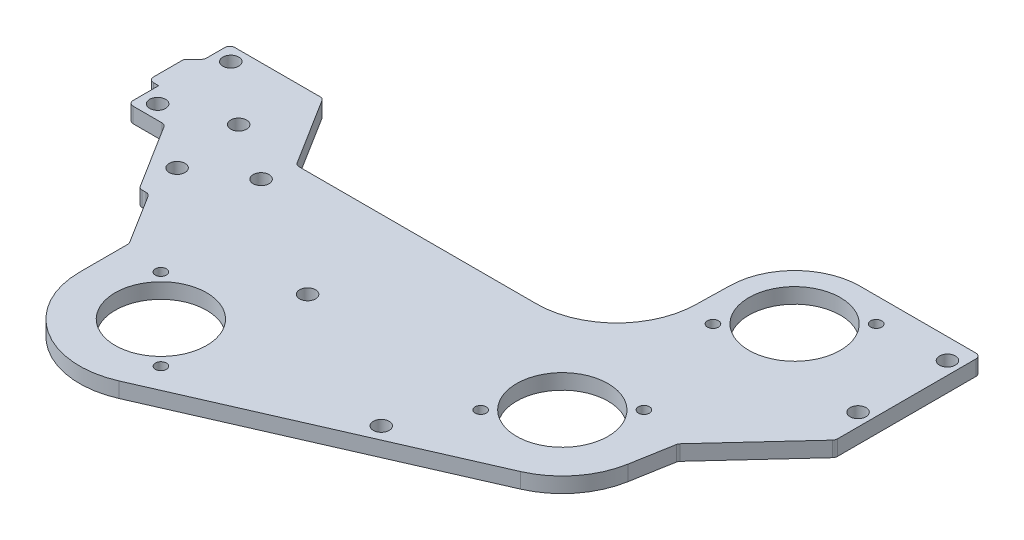
SolidWorks part; units mm, degrees
material "6061 Alloy"
ref_plane "Front Plane" through (0, 0, 0) normal (0, 0, 1) x (1, 0, 0)
ref_plane "Top Plane" through (0, 0, 0) normal (0, 1, 0) x (1, 0, 0)
ref_plane "Right Plane" through (0, 0, 0) normal (1, 0, 0) x (0, 0, -1)
sketch "Sketch1" plane through (0, 0, 0) normal (0, 1, 0) x (1, 0, 0)
  line L1 (-62.0382, -79.8833) -> (25.1671, -41.6958)
  line L5 (39.9402, -22.8907) -> (42.2751, -9.5867)
  line L6 (42.2751, -9.5867) -> (65.831, 16.0128)
  line L16 (-92.7762, 6.1643) -> (-17.7344, 6.1643)
  line L19 (65.831, 61.4936) -> (28.0466, 61.4936)
  line L20 (65.831, 16.0128) -> (65.831, 61.4936)
  line L24 (-218.6325, 207.5765) -> (-97.2237, 13.2819) construction
  line L25 (-106.6713, 28.4011) -> (-92.7762, 6.1643)
  line L26 (-72.2583, -56.6285) -> (15.031, -18.5085) construction
  line L27 (-72.2269, -82.0164) -> (109.3231, -82.0164) construction
  line L28 (15.0167, -18.5164) -> (15.0167, -82.0164) construction
  line L29 (7.3775, 31.2763) -> (7.6, 41.2639)
  line L33 (-110.9585, -24.6526) -> (-138.654, 19.6694) construction
  line L34 (-110.9585, -24.6526) -> (-126.1313, -0.371) construction
  line L36 (-135.7546, 28.4011) -> (-106.6713, 28.4011)
  line L37 (-97.6599, -56.6285) -> (-97.6599, -41.1417)
  line L38 (-107.9634, -24.6526) -> (-97.6599, -41.1417)
  line L40 (-107.9634, -24.6526) -> (-110.9585, -24.6526)
  line L42 (-138.9296, 17.2827) -> (-138.9296, 6.1643)
  line L43 (-92.7762, 6.1643) -> (-138.9296, 6.1643) construction
  line L44 (-138.9296, 6.1643) -> (-135.7546, 6.1643)
  line L45 (-135.7546, 6.1643) -> (-135.7546, -3.3607)
  line L46 (-135.7546, -3.3607) -> (-124.2632, -3.3607)
  line L47 (-124.2632, -3.3607) -> (-110.9585, -24.6526)
  line L48 (-135.7546, 6.1643) -> (-135.7546, 28.4011) construction
  line L49 (-138.9296, 17.2827) -> (-135.7546, 20.4577)
  line L50 (-135.7546, 20.4577) -> (-135.7546, 28.4011)
  circle A0 centre (28.0466, 41.0458) radius 14.29
  circle A1 centre (15.031, -18.5085) radius 14.29
  circle A2 centre (-72.2583, -56.6285) radius 14.29
  arc A4 (39.9402, -22.8907) -> (25.1671, -41.6958) centre (15.0167, -18.5164) cw
  circle A7 centre (15.031, -18.5085) radius 25.4 construction
  circle A8 centre (-72.2583, -56.6285) radius 25.4 construction
  circle A9 centre (-28.6137, -37.5685) radius 22.225 construction
  circle A10 centre (28.0466, 41.0458) radius 30.48 construction
  circle A11 centre (15.031, -18.5085) radius 30.48 construction
  arc A14 (-17.7344, 6.1643) -> (7.3775, 31.2763) centre (-17.7344, 31.2763) ccw
  arc A15 (7.6, 41.2639) -> (28.0466, 61.4936) centre (28.0466, 41.0458) cw
  arc A16 (-62.0382, -79.8833) -> (-97.6599, -56.6285) centre (-72.2583, -56.6285) cw
  point P11 (-62.0382, -79.8833)
  point P34 (15.0167, -18.5164)
  point P35 (28.0466, 41.0458)
  dimension "D2" = 50.8
  dimension "D3" = 50.8
  dimension "D4" = 44.45
  dimension "D5" = 63.5
  dimension "D7" = 60.96
  dimension "D8" = 60.96
  dimension "D1" = 140.0048
  dimension "D6" = 95.25
  dimension "D9" = 50.8
  dimension "D10" = 143.51
extrude "Boss-Extrude1" add sketch "Sketch1" along normal blind 4.7625
hole_wizard "#10 Clearance Hole1" positions "Sketch2" profile "Sketch3" hole size "#10" standard "ANSI Inch" end condition through all
sketch "Sketch2" plane through (0, 4.7625, 0) normal (0, 1, 0) x (1, 0, 0)
  point P0 (61.8305, 55.0243)
  point P3 (61.8305, 27.0843)
  point P7 (-130.9921, 23.9443)
  point P10 (-130.9921, 1.0843)
sketch "Sketch3" plane through (61.8305, 4.7625, -55.0243) normal (1, 0, 0) x (0, 0, 1)
  line L0 (0, 0) -> (0, 4.7625)
  line L1 (0, 4.7625) -> (2.4892, 4.7625)
  line L2 (2.4892, 4.7625) -> (2.4892, 0)
  line L5 (2.4892, 0) -> (0, 0)
  line L11 (0, -6.35) -> (0, 107.95) construction
  dimension "Thru Hole Dia." = 4.9784
  dimension "Thru Hole Depth" = 4.7625
sketch "Sketch4" plane through (0, 4.7625, 0) normal (0, 1, 0) x (1, 0, 0)
  line L0 (-72.2583, -56.6285) -> (-102.5432, -8.1625) construction
  line L1 (-102.5432, -8.1625) -> (-94.4656, -3.115) construction
  line L2 (-102.5432, -8.1625) -> (-110.6209, -13.21) construction
  line L3 (-102.5432, -8.1625) -> (-112.7324, 8.1436) construction
  line L4 (-102.5432, -8.1625) -> (-174.2713, 106.6264) construction
  line L5 (65.831, 41.0543) -> (65.831, 28.3543) construction
  dimension "D1" = 57.15
  dimension "D2" = 19.05
  dimension "D3" = 32
hole_wizard "#10 Clearance Hole2" positions "Sketch5" profile "Sketch6" hole size "#10" standard "ANSI Inch" end condition through all
sketch "Sketch5" plane through (0, 4.7625, 0) normal (0, 1, 0) x (1, 0, 0)
  point P0 (-110.6209, -13.21)
  point P3 (-94.4656, -3.115)
  point P7 (-112.7324, 8.1436)
sketch "Sketch6" plane through (-110.6209, 4.7625, 13.21) normal (1, 0, 0) x (0, 0, 1)
  line L0 (0, 0) -> (0, 4.7625)
  line L1 (0, 4.7625) -> (2.4892, 4.7625)
  line L2 (2.4892, 4.7625) -> (2.4892, 0)
  line L5 (2.4892, 0) -> (0, 0)
  line L11 (0, -6.35) -> (0, 107.95) construction
  dimension "Thru Hole Dia." = 4.9784
  dimension "Thru Hole Depth" = 4.7625
sketch "Sketch7" plane through (0, 4.7625, 0) normal (0, 1, 0) x (1, 0, 0)
  line L0 (-59.5064, -69.3804) -> (-85.0103, -43.8765) construction
  line L1 (2.279, -31.2604) -> (27.783, -5.7565) construction
  line L3 (15.2946, 28.2939) -> (40.7985, 53.7978) construction
  point P7 (-72.2583, -56.6285)
  point P11 (15.031, -18.5085)
  point P13 (28.0466, 41.0458)
hole_wizard "Tap Drill for #8-32 Tap1" positions "Sketch8" profile "Sketch9" hole size "#8-32" standard "ANSI Inch" end condition through all
sketch "Sketch8" plane through (0, 4.7625, 0) normal (0, 1, 0) x (1, 0, 0)
  point P0 (-85.0103, -43.8765)
  point P3 (-59.5064, -69.3804)
  point P6 (2.279, -31.2604)
  point P9 (27.783, -5.7565)
  point P12 (15.2946, 28.2939)
  point P15 (40.7985, 53.7978)
sketch "Sketch9" plane through (-85.0103, 4.7625, 43.8765) normal (1, 0, 0) x (0, 0, 1)
  line L0 (0, 0) -> (0, 4.7625)
  line L1 (0, 4.7625) -> (1.7272, 4.7625)
  line L2 (1.7272, 4.7625) -> (1.7272, 0)
  line L5 (1.7272, 0) -> (0, 0)
  line L11 (0, -6.35) -> (0, 107.95) construction
  dimension "Thru Hole Dia." = 3.4544
  dimension "Thru Hole Depth" = 4.7625
hole_wizard "#10 Clearance Hole3" positions "Sketch11" profile "Sketch12" hole size "#10" standard "ANSI Inch" end condition through all
sketch "Sketch11" plane through (0, 4.7625, 0) normal (0, 1, 0) x (1, 0, 0)
  point P0 (-56.0414, -27.0192)
  point P3 (-8.9513, -51.0906)
sketch "Sketch12" plane through (-56.0414, 4.7625, 27.0192) normal (1, 0, 0) x (0, 0, 1)
  line L0 (0, 0) -> (0, 4.7625)
  line L1 (0, 4.7625) -> (2.4892, 4.7625)
  line L2 (2.4892, 4.7625) -> (2.4892, 0)
  line L5 (2.4892, 0) -> (0, 0)
  line L11 (0, -6.35) -> (0, 107.95) construction
  dimension "Thru Hole Dia." = 4.9784
  dimension "Thru Hole Depth" = 4.7625
fillet "Fillet1" radius 1.5875 14 edges at (-135.7546, 2.3813, 3.3607) (-124.2632, 2.3813, 3.3607) (65.831, 2.3813, -61.4936) (65.831, 2.3813, -16.0128) (42.2751, 2.3813, 9.5867) (-97.6599, 2.3813, 41.1417) (-92.7762, 2.3813, -6.1643) (-106.6713, 2.3813, -28.4011) (-138.9296, 2.3813, -17.2827) (-107.9634, 2.3813, 24.6526) (-110.9585, 2.3813, 24.6526) (-135.7546, 2.3813, -28.4011) (-135.7546, 2.3813, -20.4577) (-138.9296, 2.3813, -6.1643)
